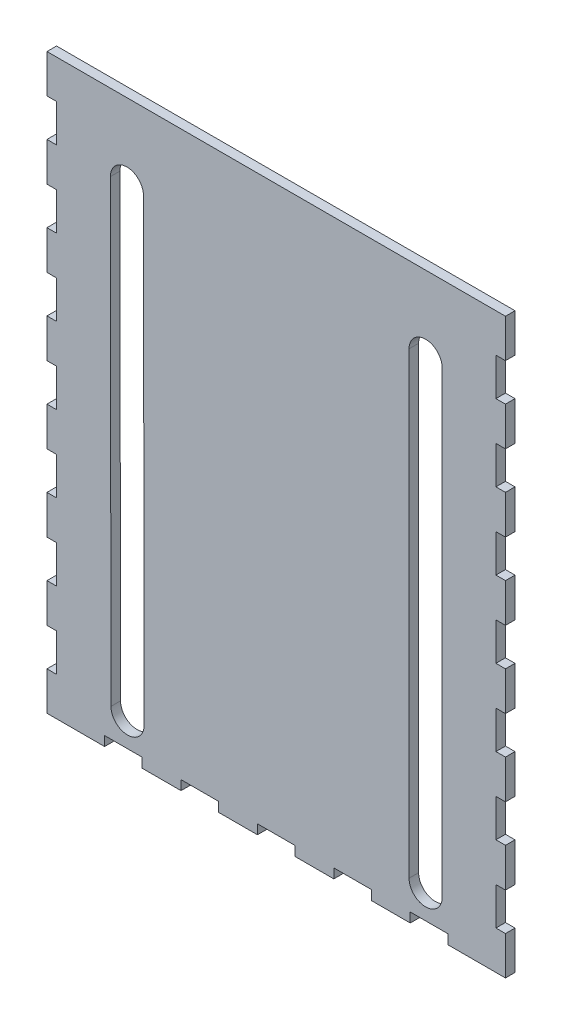
SolidWorks part; units mm, degrees
ref_plane "Front Plane" through (0, 0, 0) normal (0, 0, 1) x (1, 0, 0)
ref_plane "Top Plane" through (0, 0, 0) normal (0, 1, 0) x (1, 0, 0)
ref_plane "Right Plane" through (0, 0, 0) normal (1, 0, 0) x (0, 0, -1)
sketch "Sketch1" plane through (0, 0, 0) normal (0, 0, 1) x (1, 0, 0)
  line L1 (0, 0) -> (304.8, 0)
  line L2 (0, 0) -> (0, -381)
  line L3 (0, -381) -> (304.8, -381)
  line L4 (304.8, 0) -> (304.8, -381)
extrude "Boss-Extrude1" add sketch "Sketch1" along normal blind 6.35
sketch "Sketch2" plane through (0, 0, 0) normal (0, 0, 1) x (1, 0, 0)
  line L0 (298.45, -25.5905) -> (304.8, -25.5905)
  line L1 (0, 0) -> (0, -381) construction
  line L2 (298.45, -25.5905) -> (298.45, -50.6095)
  line L5 (240.7095, -50.8) -> (240.7095, -355.6)
  line L7 (262.7312, -50.8) -> (262.7312, -355.6)
  line L9 (298.45, -50.6095) -> (304.8, -50.6095)
  line L10 (0, -25.5905) -> (6.35, -25.5905)
  line L11 (0, -25.5905) -> (0, -50.6095)
  line L12 (0, -50.6095) -> (6.35, -50.6095)
  line L13 (6.35, -25.5905) -> (6.35, -50.6095)
  line L14 (304.8, -25.5905) -> (304.8, -50.6095)
  line L15 (298.45, -76.3905) -> (304.8, -76.3905)
  line L16 (298.45, -76.3905) -> (298.45, -101.4095)
  line L17 (298.45, -101.4095) -> (304.8, -101.4095)
  line L18 (304.8, -76.3905) -> (304.8, -101.4095)
  line L19 (298.45, -127.1905) -> (304.8, -127.1905)
  line L20 (298.45, -127.1905) -> (298.45, -152.2095)
  line L21 (298.45, -152.2095) -> (304.8, -152.2095)
  line L22 (304.8, -127.1905) -> (304.8, -152.2095)
  line L23 (298.45, -177.9905) -> (304.8, -177.9905)
  line L24 (298.45, -177.9905) -> (298.45, -203.0095)
  line L25 (298.45, -203.0095) -> (304.8, -203.0095)
  line L26 (304.8, -177.9905) -> (304.8, -203.0095)
  line L27 (298.45, -228.7905) -> (304.8, -228.7905)
  line L28 (298.45, -228.7905) -> (298.45, -253.8095)
  line L29 (298.45, -253.8095) -> (304.8, -253.8095)
  line L30 (304.8, -228.7905) -> (304.8, -253.8095)
  line L31 (298.45, -279.5905) -> (304.8, -279.5905)
  line L32 (298.45, -279.5905) -> (298.45, -304.6095)
  line L33 (298.45, -304.6095) -> (304.8, -304.6095)
  line L34 (304.8, -279.5905) -> (304.8, -304.6095)
  line L35 (298.45, -330.3905) -> (304.8, -330.3905)
  line L36 (298.45, -330.3905) -> (298.45, -355.4095)
  line L37 (298.45, -355.4095) -> (304.8, -355.4095)
  line L38 (304.8, -330.3905) -> (304.8, -355.4095)
  line L39 (0, -76.3905) -> (6.35, -76.3905)
  line L40 (0, -76.3905) -> (0, -101.4095)
  line L41 (0, -101.4095) -> (6.35, -101.4095)
  line L42 (6.35, -76.3905) -> (6.35, -101.4095)
  line L43 (0, -127.1905) -> (6.35, -127.1905)
  line L44 (0, -127.1905) -> (0, -152.2095)
  line L45 (0, -152.2095) -> (6.35, -152.2095)
  line L46 (6.35, -127.1905) -> (6.35, -152.2095)
  line L47 (0, -177.9905) -> (6.35, -177.9905)
  line L48 (0, -177.9905) -> (0, -203.0095)
  line L49 (0, -203.0095) -> (6.35, -203.0095)
  line L50 (6.35, -177.9905) -> (6.35, -203.0095)
  line L51 (0, -228.7905) -> (6.35, -228.7905)
  line L52 (0, -228.7905) -> (0, -253.8095)
  line L53 (0, -253.8095) -> (6.35, -253.8095)
  line L54 (6.35, -228.7905) -> (6.35, -253.8095)
  line L55 (0, -279.5905) -> (6.35, -279.5905)
  line L56 (0, -279.5905) -> (0, -304.6095)
  line L57 (0, -304.6095) -> (6.35, -304.6095)
  line L58 (6.35, -279.5905) -> (6.35, -304.6095)
  line L59 (0, -330.3905) -> (6.35, -330.3905)
  line L60 (0, -330.3905) -> (0, -355.4095)
  line L61 (0, -355.4095) -> (6.35, -355.4095)
  line L62 (6.35, -330.3905) -> (6.35, -355.4095)
  line L63 (89.0905, -381) -> (114.1095, -381)
  line L64 (0, -381) -> (304.8, -381) construction
  line L65 (89.0905, -381) -> (89.0905, -374.65)
  line L66 (38.2905, -381) -> (63.3095, -381)
  line L67 (38.2905, -381) -> (38.2905, -374.65)
  line L68 (38.2905, -374.65) -> (63.3095, -374.65)
  line L69 (63.3095, -381) -> (63.3095, -374.65)
  line L70 (89.0905, -374.65) -> (114.1095, -374.65)
  line L71 (114.1095, -381) -> (114.1095, -374.65)
  line L72 (139.8905, -381) -> (164.9095, -381)
  line L73 (139.8905, -381) -> (139.8905, -374.65)
  line L74 (139.8905, -374.65) -> (164.9095, -374.65)
  line L75 (164.9095, -381) -> (164.9095, -374.65)
  line L76 (190.6905, -381) -> (215.7095, -381)
  line L77 (190.6905, -381) -> (190.6905, -374.65)
  line L78 (190.6905, -374.65) -> (215.7095, -374.65)
  line L79 (215.7095, -381) -> (215.7095, -374.65)
  line L80 (241.4905, -381) -> (266.5095, -381)
  line L81 (241.4905, -381) -> (241.4905, -374.65)
  line L82 (241.4905, -374.65) -> (266.5095, -374.65)
  line L83 (266.5095, -381) -> (266.5095, -374.65)
  line L86 (42.1366, -50.9471) -> (42.543, -355.7468)
  line L87 (64.1584, -50.9177) -> (64.5648, -355.7174)
  arc A0 (262.7312, -50.8) -> (240.7095, -50.8) centre (251.7204, -50.8) ccw
  arc A4 (240.7095, -355.6) -> (262.7312, -355.6) centre (251.7204, -355.6) ccw
  arc A5 (64.5648, -355.7174) -> (42.543, -355.7468) centre (53.5539, -355.7321) cw
  arc A6 (42.1366, -50.9471) -> (64.1584, -50.9177) centre (53.1475, -50.9324) cw
  point P5 (89.0905, -377.825)
  point P14 (0, 0)
  point P16 (0, 0)
  point P17 (0, 0)
  point P18 (0, 0)
  dimension "D1" = 25.019
  dimension "D12" = 38.2905
  dimension "D2" = 11.0109
  dimension "D3" = 2
  dimension "D4" = 7
  dimension "D5" = 25.5905
  dimension "D6" = 25.019
  dimension "D7" = 25.781
  dimension "D8" = 6.35
  dimension "D10" = 25.019
  dimension "D11" = 25.781
  dimension "D9" = 5
extrude "Cut-Extrude3" cut sketch "Sketch2" along normal blind 6.35
